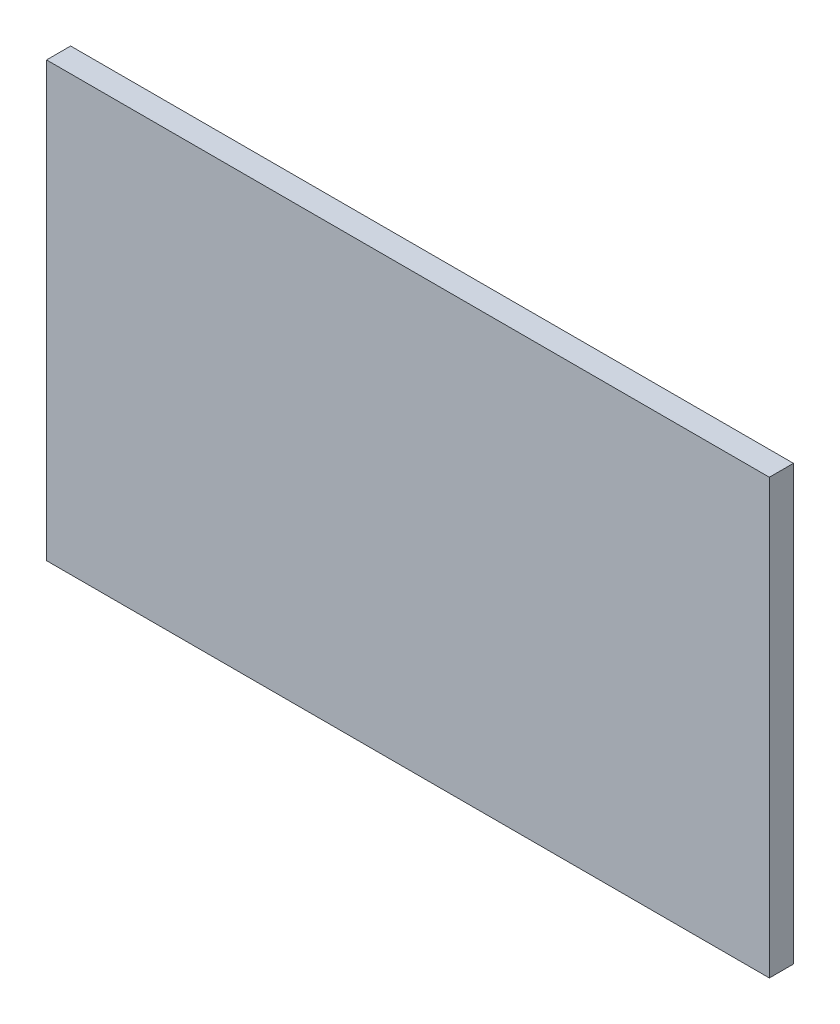
SolidWorks part; units mm, degrees
ref_plane "Front Plane" through (0, 0, 0) normal (0, 0, 1) x (1, 0, 0)
ref_plane "Top Plane" through (0, 0, 0) normal (0, 1, 0) x (1, 0, 0)
ref_plane "Right Plane" through (0, 0, 0) normal (1, 0, 0) x (0, 0, -1)
sketch "Sketch1" plane through (0, 0, 0) normal (0, 0, 1) x (1, 0, 0)
  line L1 (0, 0) -> (300, 0)
  line L2 (0, 0) -> (0, 180)
  line L3 (0, 180) -> (300, 180)
  line L4 (300, 0) -> (300, 180)
  dimension "D1" = 180
  dimension "D2" = 300
extrude "Boss-Extrude1" add sketch "Sketch1" along normal blind 10
